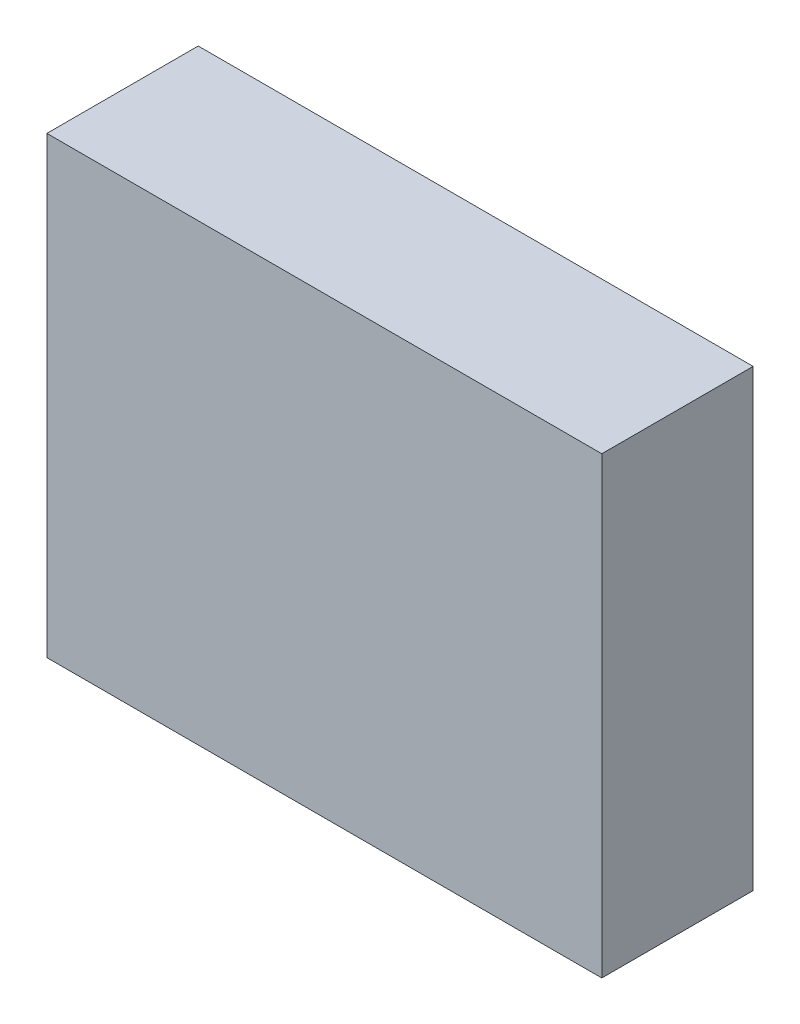
SolidWorks part; units mm, degrees
ref_plane "Front Plane" through (0, 0, 0) normal (0, 0, 1) x (1, 0, 0)
ref_plane "Top Plane" through (0, 0, 0) normal (0, 1, 0) x (1, 0, 0)
ref_plane "Right Plane" through (0, 0, 0) normal (1, 0, 0) x (0, 0, -1)
other "Configuration Table"
sketch "Sketch1" plane through (0, 0, 0) normal (0, 0, 1) x (1, 0, 0)
  line L1 (1120, 1690) -> (1230, 1690)
  line L2 (1120, 1690) -> (1120, 1780)
  line L3 (1120, 1780) -> (1230, 1780)
  line L4 (1230, 1690) -> (1230, 1780)
extrude "STORE_pano_role_karti_2_8kanal_1" add sketch "Sketch1" against normal blind 30 from offset 670 separate body
